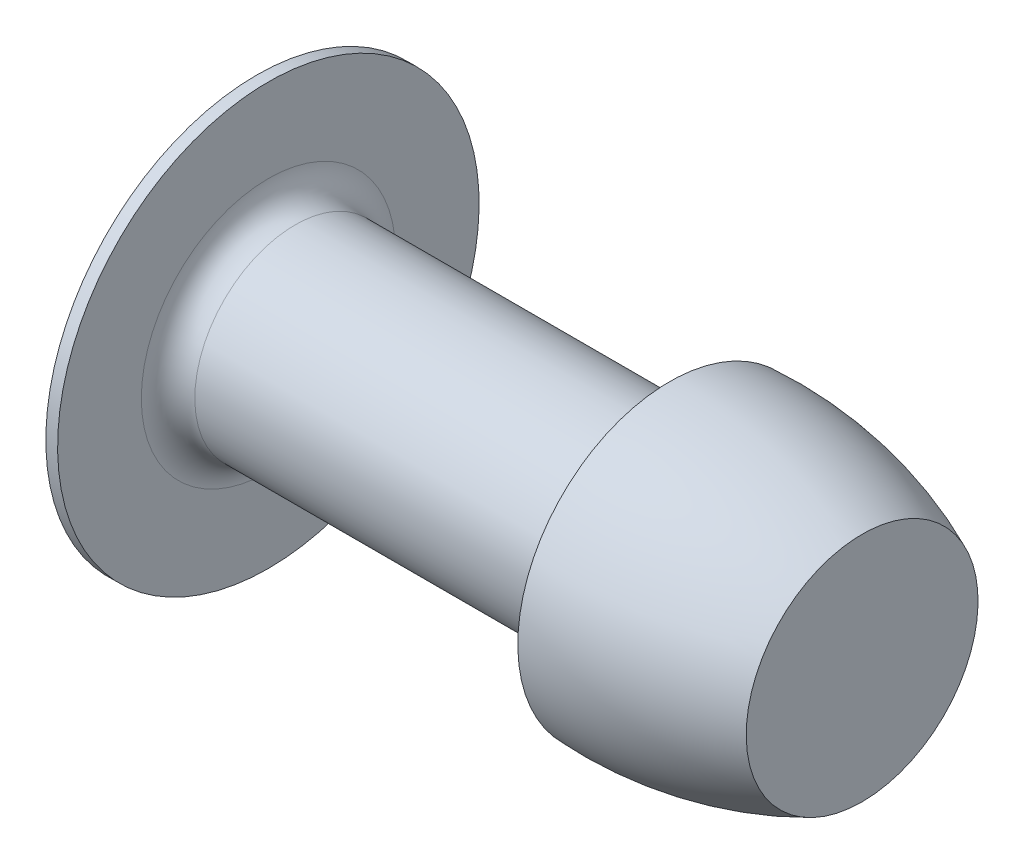
SolidWorks part; units mm, degrees
ref_plane "Front" through (0, 0, 0) normal (0, 0, 1) x (1, 0, 0)
ref_plane "Top" through (0, 0, 0) normal (0, 1, 0) x (1, 0, 0)
ref_plane "Right" through (0, 0, 0) normal (1, 0, 0) x (0, 0, -1)
ref_plane "Plane1"
sketch "Sketch1" plane through (0, 0, 0) normal (0, 0, 1) x (1, 0, 0)
  line L0 (-0.2794, 5.0038) -> (0, 5.0038)
  line L1 (0, 5.0038) -> (0, 2.3813)
  line L2 (0, 2.3813) -> (9.526, 2.3813)
  line L3 (9.526, 2.3813) -> (9.526, 3.6027)
  line L4 (14.098, 2.7521) -> (14.098, 0)
  line L5 (14.098, 0) -> (-1.524, 0)
  line L6 (-1.524, 0) -> (14.098, 0) construction
  arc A0 (14.098, 2.7521) -> (9.526, 3.6027) centre (10.0315, -6.3921) ccw
  arc A1 (-0.2794, 5.0038) -> (-1.524, 0) centre (9.157, 0) ccw
  dimension "D5" = 10.0076
  dimension "D10" = 10.681
  dimension "D1" = 5.0038
  dimension "D2" = 2.3812
  dimension "D3" = 2.7521
  dimension "D7" = 9.526
  dimension "D8" = 0.2794
  dimension "D11" = 10.0315
  dimension "D12" = 14.098
revolve "Body" add sketch "Sketch1" angle 360 about L6
fillet "Fillet1" radius 0.635 1 edges at (0, -2.3812, 0)
